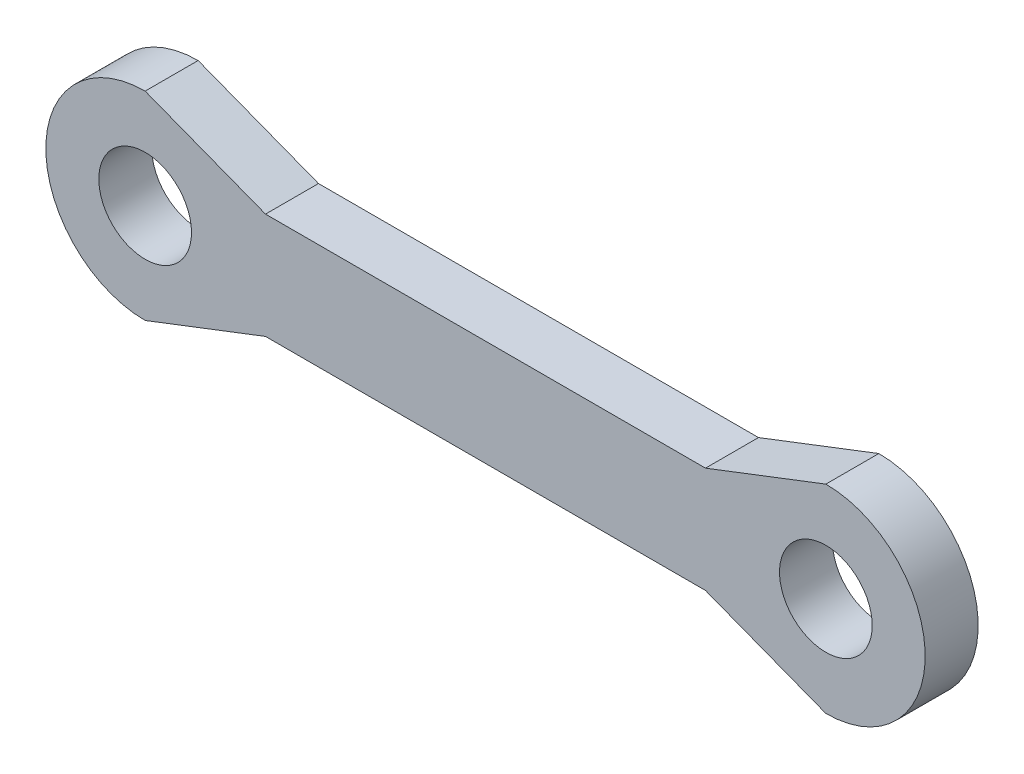
SolidWorks part; units mm, degrees
ref_plane "Ön Düzlem" through (0, 0, 0) normal (0, 0, 1) x (1, 0, 0)
ref_plane "Üst Düzlem" through (0, 0, 0) normal (0, 1, 0) x (1, 0, 0)
ref_plane "Sağ Düzlem" through (0, 0, 0) normal (1, 0, 0) x (0, 0, -1)
sketch "Sketch1" plane through (0, 0, 0) normal (0, 0, 1) x (1, 0, 0)
  line L2 (0, 7.5) -> (-9.0884, 4)
  line L3 (0, -7.5) -> (-9.0884, -4)
  line L5 (-42.3116, 4) -> (-9.0884, 4)
  line L6 (-51.4, -7.5) -> (-42.3116, -4)
  line L8 (-51.4, 7.5) -> (-42.3116, 4)
  line L9 (-42.3116, -4) -> (-9.0884, -4)
  circle A0 centre (0, 0) radius 3.5
  arc A1 (-51.4, 7.5) -> (-51.4, -7.5) centre (-51.4, 0) ccw
  arc A2 (0, -7.5) -> (0, 7.5) centre (0, 0) ccw
  circle A3 centre (-51.4, 0) radius 3.5
  dimension "D1" = 51.4
  dimension "D2" = 7
  dimension "D3" = 15
  dimension "D4" = 15
  dimension "D5" = 7
  dimension "D6" = 8
extrude "Boss-Extrude2" add sketch "Sketch1" along normal blind 4
